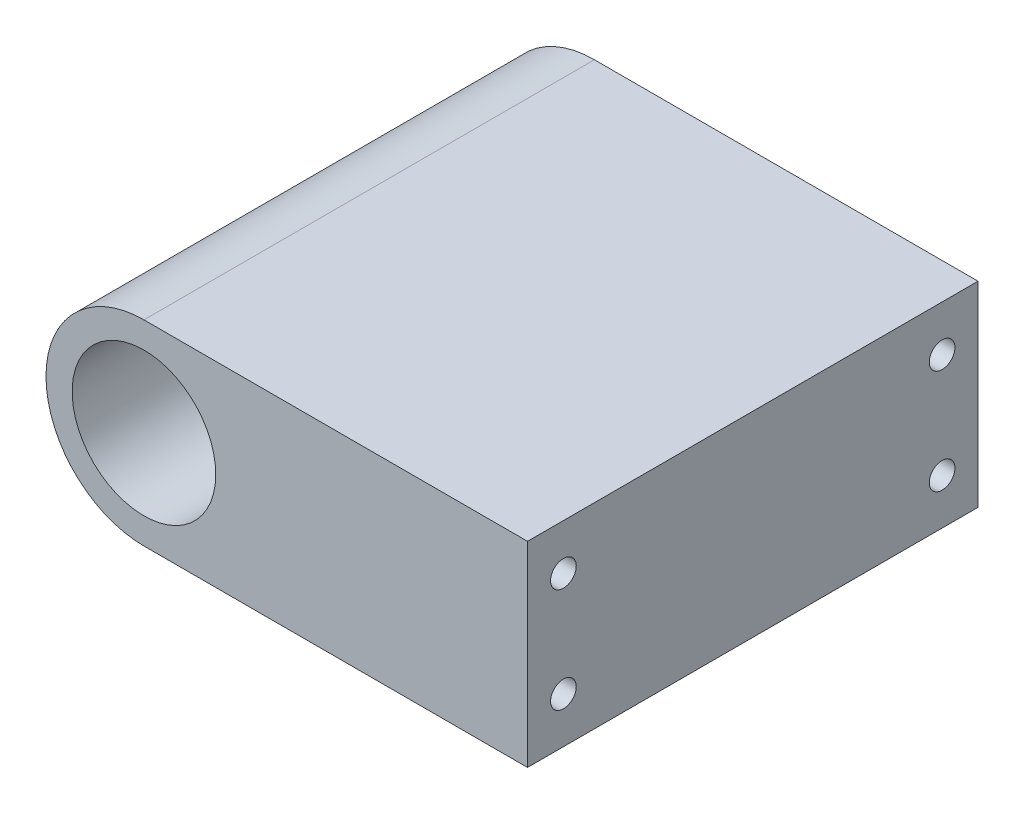
SolidWorks part; units mm, degrees
ref_plane "Front Plane" through (0, 0, 0) normal (0, 0, 1) x (1, 0, 0)
ref_plane "Top Plane" through (0, 0, 0) normal (0, 1, 0) x (1, 0, 0)
ref_plane "Right Plane" through (0, 0, 0) normal (1, 0, 0) x (0, 0, -1)
sketch "Sketch1" plane through (0, 0, 0) normal (0, 0, 1) x (1, 0, 0)
  line L0 (0, 19.05) -> (74.61, 19.05)
  line L2 (0, -27.94) -> (0, 27.94) construction
  line L3 (74.61, 19.05) -> (74.61, -19.05)
  line L4 (74.61, -19.05) -> (0, -19.05)
  line L5 (55.0055, 0) -> (-55.0055, 0) construction
  arc A0 (0, 19.05) -> (0, -19.05) centre (0, 0) ccw
  circle A1 centre (0, 0) radius 13.97
  point P6 (74.61, 0)
  dimension "D3" = 27.94
  dimension "D1" = 38.1
  dimension "D2" = 74.61
extrude "Boss-Extrude1" add sketch "Sketch1" along normal blind 87.63 contours L4 A0 L0 L3
fillet "Fillet3" radius 2.794 1 edges at (13.97, 0, 0)
sketch "Sketch2" plane through (74.61, 0, 0) normal (1, 0, 0) x (0, 0, -1)
  line L0 (-43.815, 19.05) -> (-43.815, -19.05)
  line L1 (-87.63, 19.05) -> (0, 19.05) construction
  line L2 (-87.63, -19.05) -> (0, -19.05) construction
  line L3 (-43.815, 0) -> (-88.265, 0)
  line L4 (48.895, 0) -> (-48.895, 0) construction
  line L5 (-43.815, 0) -> (0.635, 0)
  line L6 (-88.265, 0) -> (-80.645, 0)
  line L7 (-80.645, 0) -> (-80.645, 10.16)
  line L8 (-80.645, 0) -> (-80.645, -10.16)
  line L9 (0.635, 0) -> (-6.985, 0)
  line L10 (-6.985, 0) -> (-6.985, 10.16)
  line L11 (-6.985, 0) -> (-6.985, -10.16)
  point P14 (-80.645, 10.16)
  point P15 (-80.645, -10.16)
  point P17 (-6.985, 10.16)
  point P18 (-6.985, -10.16)
  point P19 (-80.645, 10.16)
  point P21 (-80.645, -10.16)
  point P23 (-81.0221, 9.179)
  dimension "D1" = 88.9
  dimension "D2" = 7.62
  dimension "D3" = 7.62
  dimension "D4" = 10.16
hole_wizard "M6x1.0 Tapped Hole1" positions "Sketch2" profile "Sketch15" tap size "M6x1.0" standard "ANSI Metric"
sketch "Sketch15" plane through (74.61, -10.16, 80.645) normal (0, 1, 0) x (0, 0, -1)
  line L0 (0, 0) -> (0, 42.6502)
  line L1 (0, 42.6502) -> (2.5, 41.148)
  line L2 (2.5, 41.148) -> (2.5, 0)
  line L5 (2.5, 0) -> (0, 0)
  line L10 (0, 42.6502) -> (-2.5, 41.148) construction
  line L11 (0, -6.35) -> (0, 107.95) construction
  dimension "Tap Drill Dia." = 5
  dimension "Tap Drill Depth" = 41.148
  dimension "Drill Angle" = 118
equation "\"rodmountsides\"= 1.5in"
equation "\"rodmountheight\"= \"plateheight\" - \"rodmountheighttolerance\"'plateheight+tolerance"
equation "\"hipplatetogearboxdiff\"= 2in"
equation "\"screwholeheightoffset\"= 0.3in"
equation "\"screwholewidthoffset\"= 0.35in"
equation "\"gearboxfacetorodmiddlediff\"= 23.81mm"
equation "\"D1@Sketch1\"=\"rodmountsides\""
equation "\"D2@Sketch1\"=\"gearboxfacetorodmiddlediff\"+\"hipplatetogearboxdiff\""
equation "\"roddiameter\"= 1in"
equation "\"rodholetolerance\"= 0.05in"
equation "\"D3@Sketch1\"=\"roddiameter\"+2*(\"rodholetolerance\")"
equation "\"D1@Boss-Extrude1\"=\"rodmountheight\""
equation "\"filetradius\"= 0.1in'filet of the rod"
equation "\"filettolerance\"= 0.01in'same as above"
equation "\"filet\"= \"filetradius\" + \"filettolerance\""
equation "\"D1@Fillet3\"=\"filet\""
equation "\"rodmountheighttolerance\"= 0.05in"
equation "\"plateheight\"= 3.5in"
equation "\"D1@Sketch2\"=\"plateheight\""
equation "\"D2@Sketch2\"=\"screwholeheightoffset\""
equation "\"D3@Sketch2\"=\"screwholeheightoffset\""
equation "\"D4@Sketch2\"=(\"rodmountsides\"/2)-\"screwholewidthoffset\""
